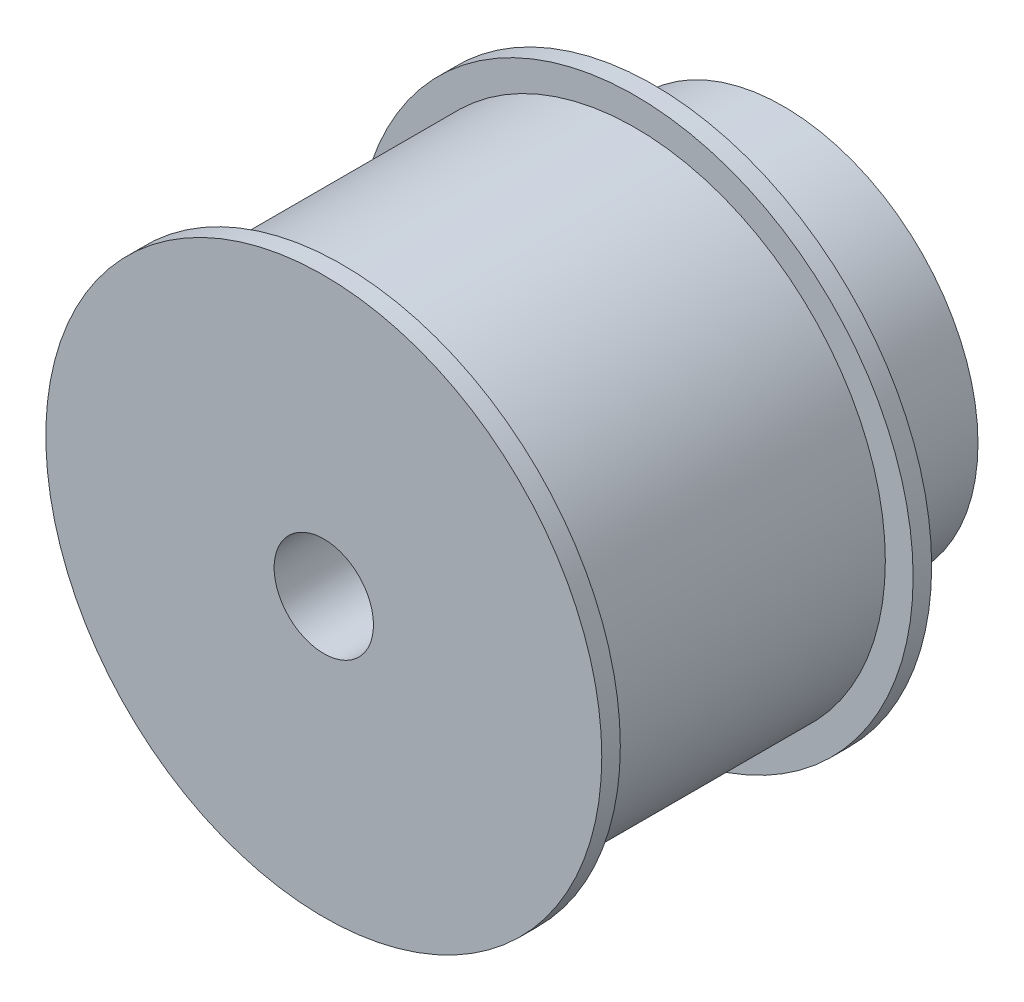
SolidWorks part; units mm, degrees
ref_plane "Front Plane" through (0, 0, 0) normal (0, 0, 1) x (1, 0, 0)
ref_plane "Top Plane" through (0, 0, 0) normal (0, 1, 0) x (1, 0, 0)
ref_plane "Right Plane" through (0, 0, 0) normal (1, 0, 0) x (0, 0, -1)
sketch "Sketch1" plane through (0, 0, 0) normal (1, 0, 0) x (0, 0, -1)
  line L0 (0, 0) -> (24.8, 0) construction
  line L1 (0, 0) -> (0, 3.6532) construction
  line L2 (0, 2.68) -> (0, 15)
  line L3 (0, 15) -> (1, 15)
  line L4 (1, 15) -> (1, 13.5)
  line L5 (1, 13.5) -> (16.8, 13.5)
  line L6 (16.8, 13.5) -> (16.8, 15)
  line L7 (16.8, 15) -> (17.8, 15)
  line L8 (17.8, 15) -> (17.8, 10.5)
  line L9 (17.8, 10.5) -> (24.8, 10.5)
  line L10 (24.8, 10.5) -> (24.8, 2.68)
  line L11 (24.8, 2.68) -> (0, 2.68)
  point P14 (0, 0)
  point P15 (0, 0)
  point P16 (0, 0)
  dimension "D1" = 2.68
  dimension "D2" = 10.5
  dimension "D3" = 15
  dimension "D4" = 13.5
  dimension "D5" = 7
  dimension "D6" = 24.8
  dimension "D7" = 1
  dimension "D8" = 1
revolve "Revolve1" add sketch "Sketch1" angle 360 about L0
